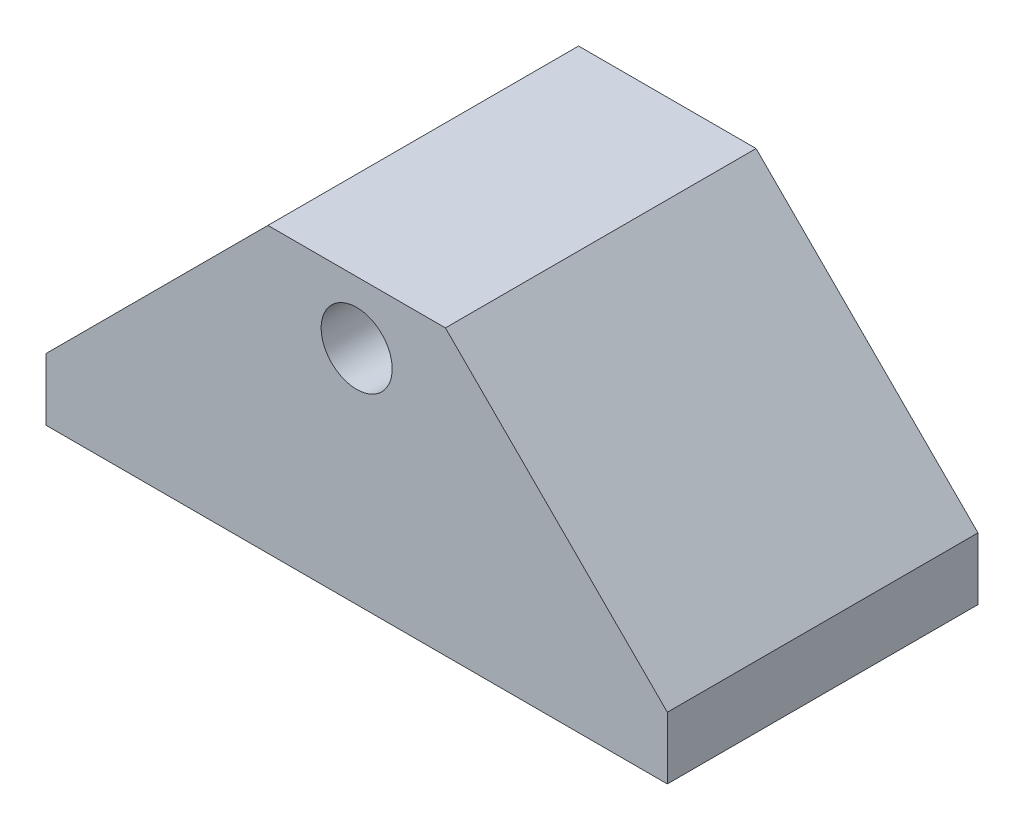
SolidWorks part; units mm, degrees
ref_plane "Front Plane" through (0, 0, 0) normal (0, 0, 1) x (1, 0, 0)
ref_plane "Top Plane" through (0, 0, 0) normal (0, 1, 0) x (1, 0, 0)
ref_plane "Right Plane" through (0, 0, 0) normal (1, 0, 0) x (0, 0, -1)
sketch "Sketch1" plane through (0, 0, 0) normal (0, 1, 0) x (1, 0, 0)
  line L1 (-35, -17.5) -> (35, -17.5)
  line L2 (-35, -17.5) -> (-35, 17.5)
  line L3 (-35, 17.5) -> (35, 17.5)
  line L4 (35, -17.5) -> (35, 17.5)
  line L5 (-35, -17.5) -> (35, 17.5) construction
  line L6 (-35, 17.5) -> (35, -17.5) construction
  point P0 (0, 0)
  dimension "D1" = 35
  dimension "D2" = 70
extrude "Boss-Extrude1" add sketch "Sketch1" along normal blind 32
sketch "Sketch2" plane through (0, 0, 17.5) normal (0, 0, 1) x (1, 0, 0)
  circle A0 centre (0, 25) radius 4
  dimension "D1" = 8
  dimension "D2" = 25
extrude "Cut-Extrude1" cut sketch "Sketch2" against normal through all
chamfer "Chamfer1" distance 25 angle 45 2 edges at (35, 32, 0) (-35, 32, 0)
